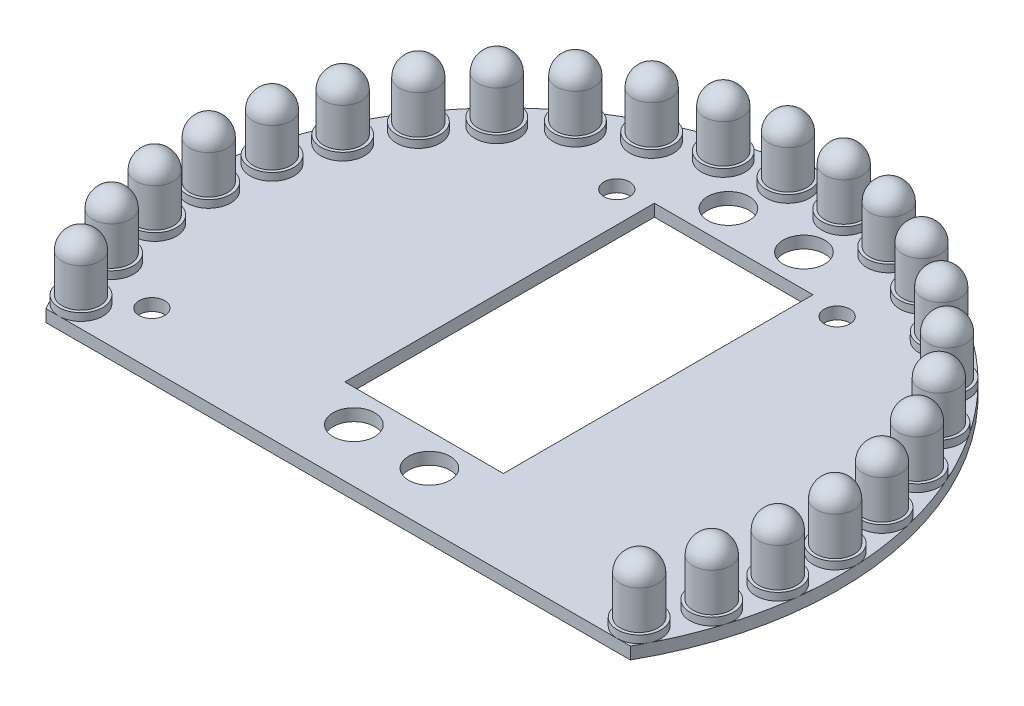
SolidWorks part; units mm, degrees
ref_plane "Front Plane" through (0, 0, 0) normal (0, 0, 1) x (1, 0, 0)
ref_plane "Top Plane" through (0, 0, 0) normal (0, 1, 0) x (1, 0, 0)
ref_plane "Right Plane" through (0, 0, 0) normal (1, 0, 0) x (0, 0, -1)
sketch "Sketch2" plane through (0, 0, 0) normal (0, 1, 0) x (1, 0, 0)
  line L5 (-10.5, 30.5) -> (10.5, 30.5)
  line L6 (-10.5, 30.5) -> (-10.5, -10.5)
  line L7 (-10.5, -10.5) -> (10.5, -10.5)
  line L8 (10.5, 30.5) -> (10.5, -10.5)
  line L11 (0, 0) -> (-38.6911, -21.8815) construction
  line L12 (0, 0) -> (38.6911, -21.8815) construction
  line L13 (-44.45, 0) -> (44.45, 0) construction
  line L14 (-38.6911, -21.8815) -> (38.6911, -21.8815)
  arc A1 (38.6911, -21.8815) -> (-38.6911, -21.8815) centre (0, 0) ccw
  point P2 (0, 0)
  point P9 (0, 0)
  point P18 (0, 0)
  dimension "D3" = 21
  dimension "D5" = 10.5
  dimension "D6" = 10.5
  dimension "D4" = 41
  dimension "D1" = 88.9
  dimension "D2" = 29.49
  dimension "D7" = 21.8815
extrude "Boss-Extrude1" add sketch "Sketch2" along normal blind 1.6
sketch "Sketch3" plane through (0, 1.6, 0) normal (0, 1, 0) x (1, 0, 0)
  line L0 (44.45, 0) -> (-44.45, 0) construction
  line L1 (-38.6911, -21.8815) -> (38.6911, -21.8815) construction
  line L3 (0, 44.45) -> (0, 0) construction
  line L6 (0, 0) -> (-36.9609, -18.9815) construction
  circle A0 centre (0, 0) radius 41.55 construction
  circle A4 centre (-36.9609, -18.9815) radius 2.9
  arc A5 (38.6911, -21.8815) -> (-38.6911, -21.8815) centre (0, 0) ccw construction
  arc A6 (38.6911, -21.8815) -> (-38.6911, -21.8815) centre (0, 0) ccw construction
  point P17 (-36.9609, -18.9815)
  point P22 (15.8965, 34.3338)
  dimension "D1" = 27.183
  dimension "D2" = 83.1
  dimension "D3" = 5.8
extrude "Boss-Extrude3" add sketch "Sketch3" along normal blind 1
sketch "Sketch4" plane through (0, 2.6, 0) normal (0, 1, 0) x (1, 0, 0)
  circle A0 centre (-36.9609, -18.9815) radius 2.5
  circle A1 centre (-36.9609, -18.9815) radius 2.9 construction
  dimension "D1" = 5
extrude "Boss-Extrude4" add sketch "Sketch4" along normal blind 5.1
sketch "Sketch5" plane through (0, 7.7, 0) normal (0, 1, 0) x (1, 0, 0)
  line L0 (-39.4609, -18.9815) -> (-34.4609, -18.9815)
  circle A0 centre (-36.9609, -18.9815) radius 2.5 construction
  circle A1 centre (-36.9609, -18.9815) radius 2.5 construction
  arc A2 (-34.4609, -18.9815) -> (-39.4609, -18.9815) centre (-36.9609, -18.9815) ccw
revolve "Revolve1" add sketch "Sketch5" angle 180 about L0
pattern_circular "CirPattern1" count 24 over 234.36 about axis through (0, 0, 0) along (0, 1, 0) of "Boss-Extrude3", "Boss-Extrude4", "Revolve1"
sketch "Sketch6" plane through (0, 1.6, 0) normal (0, 1, 0) x (1, 0, 0)
  line L0 (0, 77.49) -> (0, 41.7628) construction
  line L1 (-10.5, 30.5) -> (10.5, 30.5) construction
  line L2 (-5, 34.8002) -> (5, 34.8002) construction
  line L3 (-0.88, 10) -> (0.88, 10) construction
  line L4 (-10.5, 30.5) -> (-10.5, -10.5) construction
  line L5 (10.5, 30.5) -> (10.5, -10.5) construction
  line L6 (-10.5, 30.5) -> (10.5, 30.5) construction
  line L7 (-10.5, -10.5) -> (10.5, -10.5) construction
  circle A5 centre (5, 34.8002) radius 2.75
  circle A6 centre (-5, 34.8002) radius 2.75
  circle A9 centre (-31.75, -14.8002) radius 1.7
  circle A10 centre (5, -14.8002) radius 2.75
  circle A11 centre (-5, -14.8002) radius 2.75
  circle A12 centre (31.75, -14.8002) radius 1.7
  circle A13 centre (14.5894, 29.611) radius 1.7
  circle A14 centre (-14.5894, 29.611) radius 1.7
  point P18 (0, 34.8002)
  point P21 (-14.5894, 29.3318)
  point P22 (14.5894, 28.5681)
  point P23 (0, 0)
  point P39 (0, -10.5)
  dimension "D1" = 3.4
  dimension "D2" = 5.5
  dimension "D3" = 4.3002
  dimension "D4" = 10
  dimension "D5" = 31.75
  dimension "D6" = 31.75
  dimension "D7" = 4.0894
  dimension "D8" = 4.0894
  dimension "D9" = 0.889
ref_plane "Plane1" through (0, 0, -10) normal (0, 0, 1) x (1, 0, 0)
extrude "Cut-Extrude1" cut sketch "Sketch6" against normal up to surface (1.6 mm away) up to face at (0, 0, -10)
equation "\"D6@Sketch2\"=\"D3@Sketch2\"/2"
equation "\"D5@Sketch2\"=\"D3@Sketch2\"/2"
